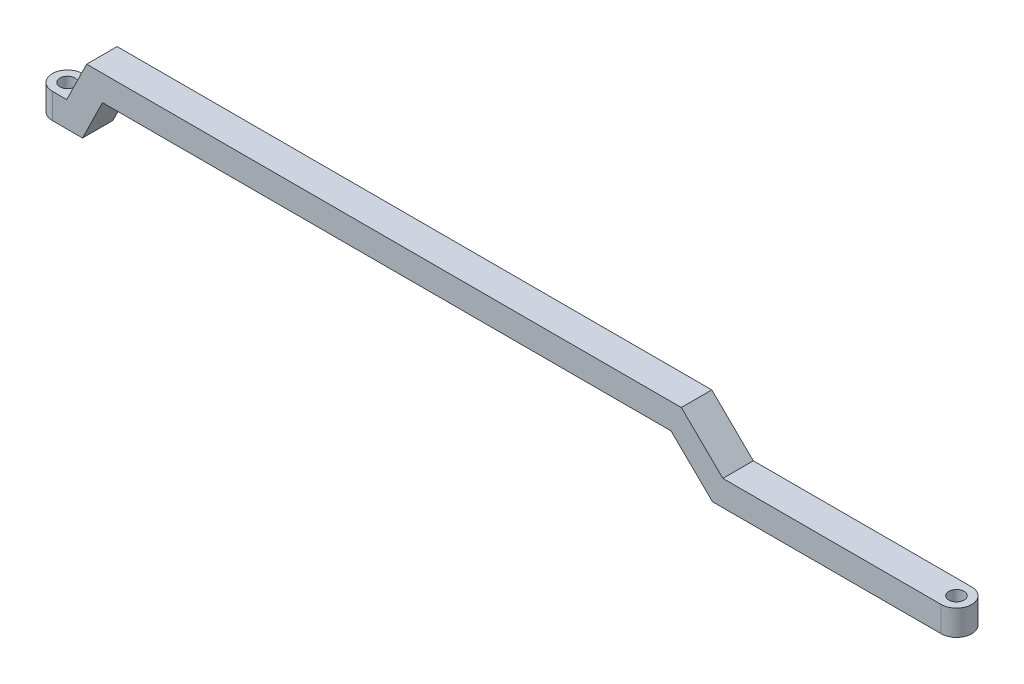
SolidWorks part; units mm, degrees
ref_plane "Alzado" through (0, 0, 0) normal (0, 0, 1) x (1, 0, 0)
ref_plane "Planta" through (0, 0, 0) normal (0, 1, 0) x (1, 0, 0)
ref_plane "Vista lateral" through (0, 0, 0) normal (1, 0, 0) x (0, 0, -1)
sketch "Croquis1" plane through (0, 0, 0) normal (0, 1, 0) x (1, 0, 0)
  line L0 (175, 3) -> (0, 3)
  line L1 (0, -3) -> (175, -3)
  circle A0 centre (0, 0) radius 1.5
  circle A1 centre (175, 0) radius 1.5
  arc A2 (175, -3) -> (175, 3) centre (175, 0) ccw
  arc A3 (0, 3) -> (0, -3) centre (0, 0) ccw
  dimension "D1" = 3
  dimension "D2" = 3
  dimension "D4" = 6
  dimension "D5" = 6
  dimension "D3" = 175
extrude "Saliente-Extruir1" add sketch "Croquis1" along normal blind 5
sketch "Croquis2" plane through (0, 0, -3) normal (0, 0, -1) x (-1, 0, 0)
  line L0 (-132.007, 5) -> (-123.8305, 13)
  line L1 (-175, 5) -> (0, 5) construction
  line L2 (-123.8305, 13) -> (-6.7652, 13)
  line L3 (-6.7652, 13) -> (-2.8406, 5)
  line L5 (-120, 5) -> (-2.8406, 5)
  line L10 (-120, 5) -> (-132.007, 5)
  point P9 (-61.4203, 5)
  dimension "D1" = 120
  dimension "D2" = 8
extrude "Saliente-Extruir2" add sketch "Croquis2" against normal blind 6
sketch "Croquis4" plane through (0, 0, -3) normal (0, 0, -1) x (-1, 0, 0)
  line L2 (-2.8406, 5) -> (-6.7652, 13) construction
  line L4 (-9.8816, 8) -> (-3.1088, -5.8061)
  line L5 (-3.1088, -5.8061) -> (-63.3385, -7.2804)
  line L7 (-121.7913, 8) -> (-136.266, -6.1623)
  line L8 (-136.266, -6.1623) -> (-63.3385, -7.2804)
  line L9 (-123.8305, 13) -> (-132.007, 5) construction
  line L10 (-9.8816, 8) -> (-121.7913, 8)
  line L11 (-6.7652, 13) -> (-123.8305, 13) construction
  dimension "D1" = 5
  dimension "D2" = 5
  dimension "D3" = 5
extrude "Cortar-Extruir2" cut sketch "Croquis4" against normal blind 22
